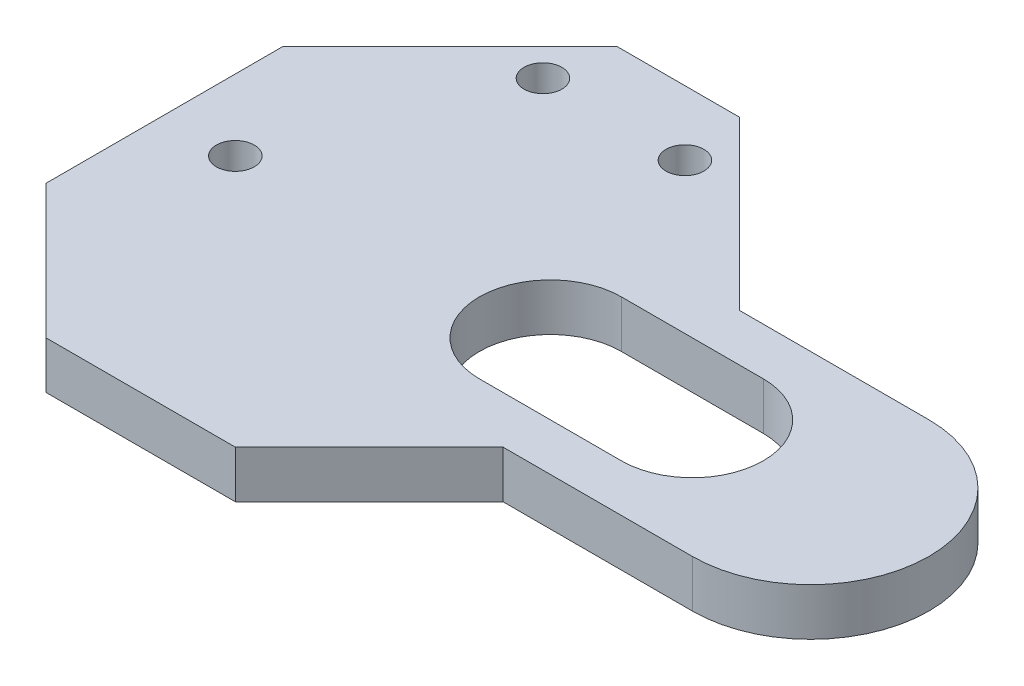
SolidWorks part; units mm, degrees
ref_plane "Front Plane" through (0, 0, 0) normal (0, 0, 1) x (1, 0, 0)
ref_plane "Top Plane" through (0, 0, 0) normal (0, 1, 0) x (1, 0, 0)
ref_plane "Right Plane" through (0, 0, 0) normal (1, 0, 0) x (0, 0, -1)
sketch "Sketch1" plane through (0, 0, 0) normal (0, 1, 0) x (1, 0, 0)
  line L0 (0, 0) -> (40, 0)
  line L1 (0, 0) -> (-28.2843, 28.2843)
  line L2 (-28.2843, 28.2843) -> (-28.2843, 78.2843)
  line L3 (-28.2843, 78.2843) -> (7.0711, 113.6396)
  line L4 (7.0711, 113.6396) -> (32.9289, 113.6396)
  line L5 (32.9289, 113.6396) -> (68.2843, 78.2843)
  line L6 (68.2843, 78.2843) -> (108.2843, 78.2843)
  line L7 (108.2843, 28.2843) -> (68.2843, 28.2843)
  line L8 (68.2843, 28.2843) -> (40, 0)
  line L9 (108.2843, 53.2843) -> (-28.2843, 53.2843) construction
  line L10 (20, 113.6396) -> (20, 0) construction
  line L11 (53.2843, 53.2843) -> (83.2843, 53.2843) construction
  line L12 (53.2843, 68.2843) -> (83.2843, 68.2843)
  line L13 (53.2843, 38.2843) -> (83.2843, 38.2843)
  line L14 (68.2843, 28.2843) -> (68.2843, 78.2843) construction
  line L15 (68.2843, 68.2843) -> (68.2843, 38.2843) construction
  arc A0 (108.2843, 78.2843) -> (108.2843, 28.2843) centre (108.2843, 53.2843) cw
  circle A1 centre (5, 100) radius 4
  circle A2 centre (35, 100) radius 4
  circle A3 centre (-13.2843, 53.2843) radius 4
  arc A4 (53.2843, 68.2843) -> (53.2843, 38.2843) centre (53.2843, 53.2843) ccw
  arc A5 (83.2843, 38.2843) -> (83.2843, 68.2843) centre (83.2843, 53.2843) ccw
  point P23 (68.2843, 53.2843)
  dimension "D8" = 8
  dimension "D1" = 40
  dimension "D2" = 50
  dimension "D3" = 40
  dimension "D4" = 45
  dimension "D5" = 50
  dimension "D6" = 45
  dimension "D7" = 40
  dimension "D9" = 15
  dimension "D10" = 100
  dimension "D11" = 30
  dimension "D12" = 30
  dimension "D13" = 30
extrude "Boss-Extrude1" add sketch "Sketch1" along normal blind 10
sketch "Sketch2" plane through (0, 10, 0) normal (0, 1, 0) x (1, 0, 0)
  line L0 (68.2843, 68.2843) -> (68.2843, 38.2843) construction
  line L1 (83.2843, 68.2843) -> (53.2843, 68.2843) construction
  line L2 (53.2843, 38.2843) -> (83.2843, 38.2843) construction
ref_plane "Plane1" through (68.2843, 0, 0) normal (-1, 0, 0) x (0, 0, 1)
sketch "Sketch3" plane through (0, 10, 0) normal (0, 1, 0) x (1, 0, 0)
  line L0 (98.2843, 53.2843) -> (38.2843, 53.2843) construction
  arc A0 (83.2843, 38.2843) -> (83.2843, 68.2843) centre (83.2843, 53.2843) ccw construction
  arc A1 (53.2843, 68.2843) -> (53.2843, 38.2843) centre (53.2843, 53.2843) ccw construction
ref_plane "Plane2" through (0, 0, -53.2843) normal (0, 0, -1) x (-1, 0, 0)
